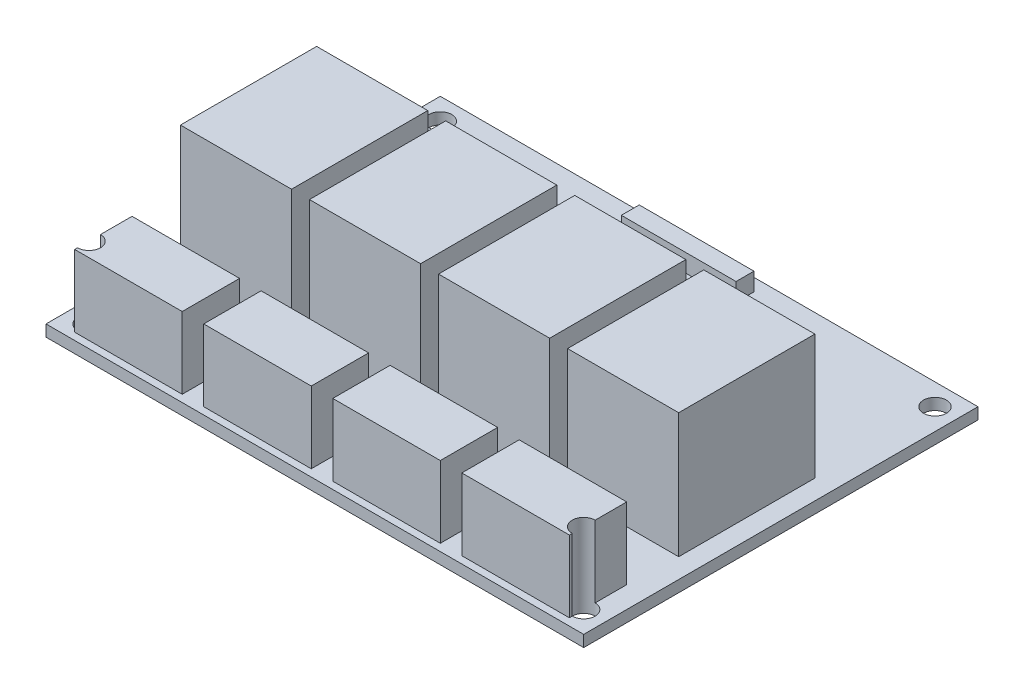
SolidWorks part; units mm, degrees
ref_plane "Front Plane" through (0, 0, 0) normal (0, 0, 1) x (1, 0, 0)
ref_plane "Top Plane" through (0, 0, 0) normal (0, 1, 0) x (1, 0, 0)
ref_plane "Right Plane" through (0, 0, 0) normal (1, 0, 0) x (0, 0, -1)
other "Configuration Table"
sketch "Sketch1" plane through (0, 0, 0) normal (0, 1, 0) x (1, 0, 0)
  line L1 (-37.5, -27.5) -> (37.5, -27.5)
  line L2 (-37.5, -27.5) -> (-37.5, 27.5)
  line L3 (-37.5, 27.5) -> (37.5, 27.5)
  line L4 (37.5, -27.5) -> (37.5, 27.5)
  line L5 (-37.5, -27.5) -> (37.5, 27.5) construction
  line L6 (-37.5, 27.5) -> (37.5, -27.5) construction
extrude "PCB" add sketch "Sketch1" along normal blind 1.6
sketch "Sketch2" plane through (0, 0, 0) normal (0, 1, 0) x (1, 0, 0)
  line L1 (-34.75, -11.5) -> (-19.25, -11.5)
  line L2 (-34.75, -11.5) -> (-34.75, 7.5)
  line L3 (-34.75, 7.5) -> (-19.25, 7.5)
  line L4 (-19.25, -11.5) -> (-19.25, 7.5)
  line L5 (-34.75, -11.5) -> (-19.25, 7.5) construction
  line L6 (-34.75, 7.5) -> (-19.25, -11.5) construction
extrude "Relay_1" add sketch "Sketch2" along normal blind 17.4 from offset 1.6
sketch "Sketch3" plane through (0, 0, 0) normal (0, 1, 0) x (1, 0, 0)
  line L1 (-34.5, -26.5) -> (-19.5, -26.5)
  line L2 (-34.5, -26.5) -> (-34.5, -18.5)
  line L3 (-34.5, -18.5) -> (-19.5, -18.5)
  line L4 (-19.5, -26.5) -> (-19.5, -18.5)
  line L5 (-34.5, -26.5) -> (-19.5, -18.5) construction
  line L6 (-34.5, -18.5) -> (-19.5, -26.5) construction
extrude "Terminal_1" add sketch "Sketch3" along normal blind 10 from offset 1.6
sketch "Sketch4" plane through (0, 0, 0) normal (0, 1, 0) x (1, 0, 0)
  line L1 (-16.75, -11.5) -> (-1.25, -11.5)
  line L2 (-16.75, -11.5) -> (-16.75, 7.5)
  line L3 (-16.75, 7.5) -> (-1.25, 7.5)
  line L4 (-1.25, -11.5) -> (-1.25, 7.5)
  line L5 (-16.75, -11.5) -> (-1.25, 7.5) construction
  line L6 (-16.75, 7.5) -> (-1.25, -11.5) construction
extrude "Relay_2" add sketch "Sketch4" along normal blind 17.4 from offset 1.6
sketch "Sketch5" plane through (0, 0, 0) normal (0, 1, 0) x (1, 0, 0)
  line L1 (-16.5, -26.5) -> (-1.5, -26.5)
  line L2 (-16.5, -26.5) -> (-16.5, -18.5)
  line L3 (-16.5, -18.5) -> (-1.5, -18.5)
  line L4 (-1.5, -26.5) -> (-1.5, -18.5)
  line L5 (-16.5, -26.5) -> (-1.5, -18.5) construction
  line L6 (-16.5, -18.5) -> (-1.5, -26.5) construction
extrude "Terminal_2" add sketch "Sketch5" along normal blind 10 from offset 1.6
sketch "Sketch6" plane through (0, 0, 0) normal (0, 1, 0) x (1, 0, 0)
  line L1 (1.25, -11.5) -> (16.75, -11.5)
  line L2 (1.25, -11.5) -> (1.25, 7.5)
  line L3 (1.25, 7.5) -> (16.75, 7.5)
  line L4 (16.75, -11.5) -> (16.75, 7.5)
  line L5 (1.25, -11.5) -> (16.75, 7.5) construction
  line L6 (1.25, 7.5) -> (16.75, -11.5) construction
extrude "Relay_3" add sketch "Sketch6" along normal blind 17.4 from offset 1.6
sketch "Sketch7" plane through (0, 0, 0) normal (0, 1, 0) x (1, 0, 0)
  line L1 (1.5, -26.5) -> (16.5, -26.5)
  line L2 (1.5, -26.5) -> (1.5, -18.5)
  line L3 (1.5, -18.5) -> (16.5, -18.5)
  line L4 (16.5, -26.5) -> (16.5, -18.5)
  line L5 (1.5, -26.5) -> (16.5, -18.5) construction
  line L6 (1.5, -18.5) -> (16.5, -26.5) construction
extrude "Terminal_3" add sketch "Sketch7" along normal blind 10 from offset 1.6
sketch "Sketch8" plane through (0, 0, 0) normal (0, 1, 0) x (1, 0, 0)
  line L1 (19.25, -11.5) -> (34.75, -11.5)
  line L2 (19.25, -11.5) -> (19.25, 7.5)
  line L3 (19.25, 7.5) -> (34.75, 7.5)
  line L4 (34.75, -11.5) -> (34.75, 7.5)
  line L5 (19.25, -11.5) -> (34.75, 7.5) construction
  line L6 (19.25, 7.5) -> (34.75, -11.5) construction
extrude "Relay_4" add sketch "Sketch8" along normal blind 17.4 from offset 1.6
sketch "Sketch9" plane through (0, 0, 0) normal (0, 1, 0) x (1, 0, 0)
  line L1 (19.5, -26.5) -> (34.5, -26.5)
  line L2 (19.5, -26.5) -> (19.5, -18.5)
  line L3 (19.5, -18.5) -> (34.5, -18.5)
  line L4 (34.5, -26.5) -> (34.5, -18.5)
  line L5 (19.5, -26.5) -> (34.5, -18.5) construction
  line L6 (19.5, -18.5) -> (34.5, -26.5) construction
extrude "Terminal_4" add sketch "Sketch9" along normal blind 10 from offset 1.6
sketch "Sketch10" plane through (0, 0, 0) normal (0, 1, 0) x (1, 0, 0)
  line L1 (-8, 23.25) -> (8, 23.25)
  line L2 (-8, 23.25) -> (-8, 25.75)
  line L3 (-8, 25.75) -> (8, 25.75)
  line L4 (8, 23.25) -> (8, 25.75)
  line L5 (-8, 23.25) -> (8, 25.75) construction
  line L6 (-8, 25.75) -> (8, 23.25) construction
extrude "Header" add sketch "Sketch10" along normal blind 2.5 from offset 1.6
sketch "Sketch11" plane through (0, 0, 0) normal (0, 1, 0) x (1, 0, 0)
  circle A0 centre (-34.5, 24.5) radius 1.6
  circle A1 centre (-34.5, -24.5) radius 1.6
  circle A2 centre (34.5, 24.5) radius 1.6
  circle A3 centre (34.5, -24.5) radius 1.6
extrude "Mount_Holes" cut sketch "Sketch11" along normal through all and the other way through all
equation "\"rly_L\"= 75.0   'ASSUMPTION: 4-ch relay board L (PDF fallback)"
equation "\"rly_W\"= 55.0   'ASSUMPTION: 4-ch relay board W (PDF fallback)"
equation "\"rly_H\"= 19.0   'ASSUMPTION: 4-ch relay board H (PDF fallback)"
equation "\"rly_hole_X\"= 69.0   'ASSUMPTION: Relay mounting hole spacing L (PDF fallback)"
equation "\"rly_hole_Y\"= 49.0   'ASSUMPTION: Relay mounting hole spacing W (PDF fallback)"
equation "\"pcb_t\"= 1.6   'ASSUMPTION: PCB thickness (standard)"
equation "\"D1@PCB\" = \"pcb_t\""
